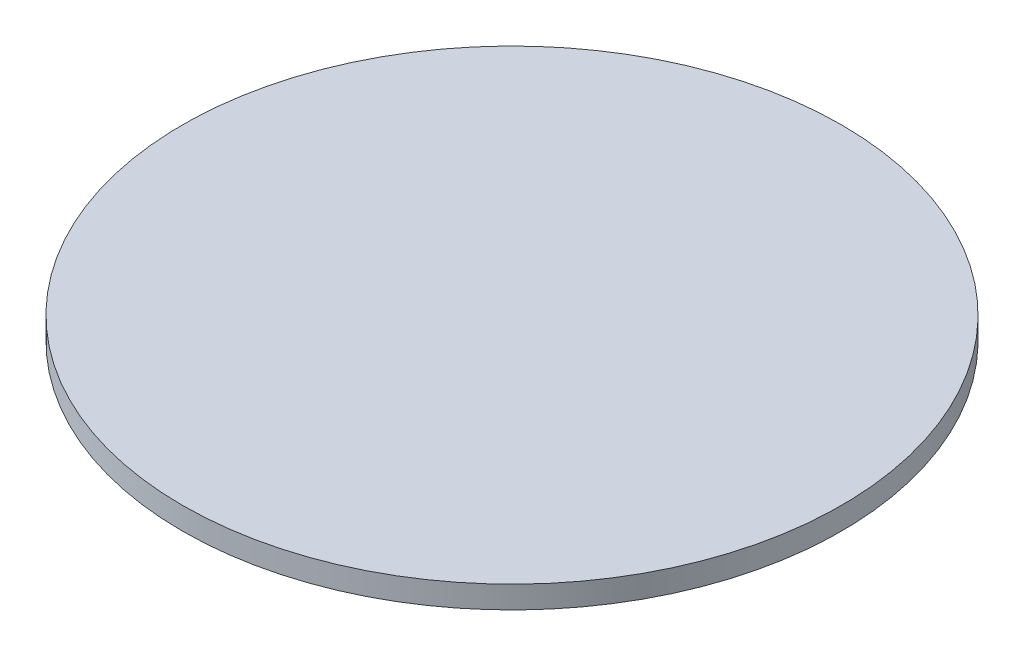
SolidWorks part; units mm, degrees
ref_plane "Front Plane" through (0, 0, 0) normal (0, 0, 1) x (1, 0, 0)
ref_plane "Top Plane" through (0, 0, 0) normal (0, 1, 0) x (1, 0, 0)
ref_plane "Right Plane" through (0, 0, 0) normal (1, 0, 0) x (0, 0, -1)
sketch "Sketch1" plane through (0, 0, 0) normal (0, 1, 0) x (1, 0, 0)
  circle A0 centre (0, 0) radius 44.2582
extrude "Boss-Extrude1" add sketch "Sketch1" along normal blind 3
